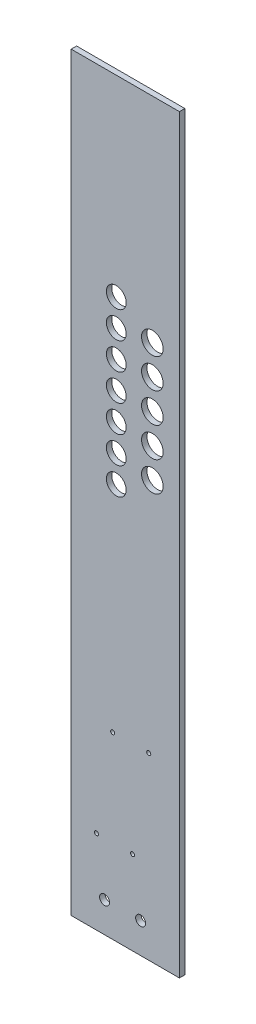
SolidWorks part; units mm, degrees
ref_plane "Plan de face" through (0, 0, 0) normal (0, 0, 1) x (1, 0, 0)
ref_plane "Plan de dessus" through (0, 0, 0) normal (0, 1, 0) x (1, 0, 0)
ref_plane "Plan de droite" through (0, 0, 0) normal (1, 0, 0) x (0, 0, -1)
sketch "Esquisse1" plane through (0, 0, 0) normal (0, 0, 1) x (1, 0, 0)
  line L1 (-60, -416) -> (60, -416)
  line L2 (-60, -416) -> (-60, 416)
  line L3 (-60, 416) -> (60, 416)
  line L4 (60, -416) -> (60, 416)
  line L5 (-60, -416) -> (60, 416) construction
  line L6 (-60, 416) -> (60, -416) construction
  point P0 (0, 0)
  dimension "D1" = 120
  dimension "D2" = 832
extrude "Boss.-Extru.1" add sketch "Esquisse1" along normal blind 6
hole_wizard "M10 Clearance Hole1" positions "Sketch2" profile "Sketch1" hole size "M10" standard "ANSI Metric" end condition through all
sketch "Sketch2" plane through (0, 0, 6) normal (0, 0, 1) x (1, 0, 0)
  point P0 (17, -382.3489)
  point P2 (-23, -382.3489)
sketch "Sketch1" plane through (17, -382.3489, 6) normal (1, 0, 0) x (0, -1, 0)
  line L0 (0, 0) -> (0, 6)
  line L1 (0, 6) -> (5.5, 6)
  line L2 (5.5, 6) -> (5.5, 0)
  line L5 (5.5, 0) -> (0, 0)
  line L11 (0, -6.35) -> (0, 107.95) construction
  dimension "Thru Hole Dia." = 11
  dimension "Thru Hole Depth" = 6
hole_wizard "M4 Clearance Hole1" positions "Sketch4" profile "Sketch3" hole size "M4" standard "ANSI Metric" end condition through all
sketch "Sketch4" plane through (0, 0, 6) normal (0, 0, 1) x (1, 0, 0)
  point P0 (26, -217)
  point P3 (8, -323)
  point P6 (-32, -323)
  point P9 (-14, -217)
sketch "Sketch3" plane through (26, -217, 6) normal (1, 0, 0) x (0, -1, 0)
  line L0 (0, 0) -> (0, 6)
  line L1 (0, 6) -> (2.25, 6)
  line L2 (2.25, 6) -> (2.25, 0)
  line L5 (2.25, 0) -> (0, 0)
  line L11 (0, -6.35) -> (0, 107.95) construction
  dimension "Thru Hole Dia." = 4.5
  dimension "Thru Hole Depth" = 6
sketch "Sketch5" plane through (0, 0, 6) normal (0, 0, 1) x (1, 0, 0)
  line L0 (40, 216) -> (-20, 216)
  line L1 (40, 216) -> (40, 10)
  line L2 (-20, 216) -> (-20, 10)
  line L3 (40, 10) -> (-20, 10)
  line L4 (-60, 416) -> (-60, -416) construction
  line L5 (60, 416) -> (-60, 416) construction
  line L6 (10, 216) -> (10, 10) construction
  line L7 (40, 113) -> (-20, 113) construction
  circle A0 centre (-10, 113) radius 3
  circle A1 centre (30, 113) radius 3
  dimension "D5" = 6
  dimension "D7" = 6
  dimension "D1" = 40
  dimension "D2" = 60
  dimension "D3" = 200
  dimension "D4" = 10
  dimension "D6" = 10
  dimension "D8" = 10
extrude "Cut-Extrude1" cut sketch "Sketch5" against normal blind 10 contours A1 | A0
hole_wizard "M20 Clearance Hole1" positions "Sketch7" profile "Sketch6" hole size "M20" standard "ANSI Metric" end condition through all
sketch "Sketch7" plane through (0, 0, 6) normal (0, 0, 1) x (1, 0, 0)
  point P0 (-10, 113)
sketch "Sketch6" plane through (-10, 113, 6) normal (1, 0, 0) x (0, -1, 0)
  line L0 (0, 0) -> (0, 6)
  line L1 (0, 6) -> (11, 6)
  line L2 (11, 6) -> (11, 0)
  line L5 (11, 0) -> (0, 0)
  line L11 (0, -6.35) -> (0, 107.95) construction
  dimension "Thru Hole Dia." = 22
  dimension "Thru Hole Depth" = 6
hole_wizard "M22 Clearance Hole1" positions "Sketch9" profile "Sketch8" hole size "M22" standard "ANSI Metric" end condition through all
sketch "Sketch9" plane through (0, 0, 6) normal (0, 0, 1) x (1, 0, 0)
  point P0 (30, 113)
sketch "Sketch8" plane through (30, 113, 6) normal (1, 0, 0) x (0, -1, 0)
  line L0 (0, 0) -> (0, 6)
  line L1 (0, 6) -> (12, 6)
  line L2 (12, 6) -> (12, 0)
  line L5 (12, 0) -> (0, 0)
  line L11 (0, -6.35) -> (0, 107.95) construction
  dimension "Thru Hole Dia." = 24
  dimension "Thru Hole Depth" = 6
pattern_linear "LPattern1" count 4 spacing 30 along (0, 1, 0) of "M20 Clearance Hole1"
pattern_linear "LPattern2" count 3 spacing 33 along (0, 1, 0) of "M22 Clearance Hole1"
pattern_linear "LPattern3" count 3 spacing 33 along (0, -1, 0) of "M22 Clearance Hole1"
pattern_linear "LPattern4" count 4 spacing 30 along (0, -1, 0) of "M20 Clearance Hole1"
